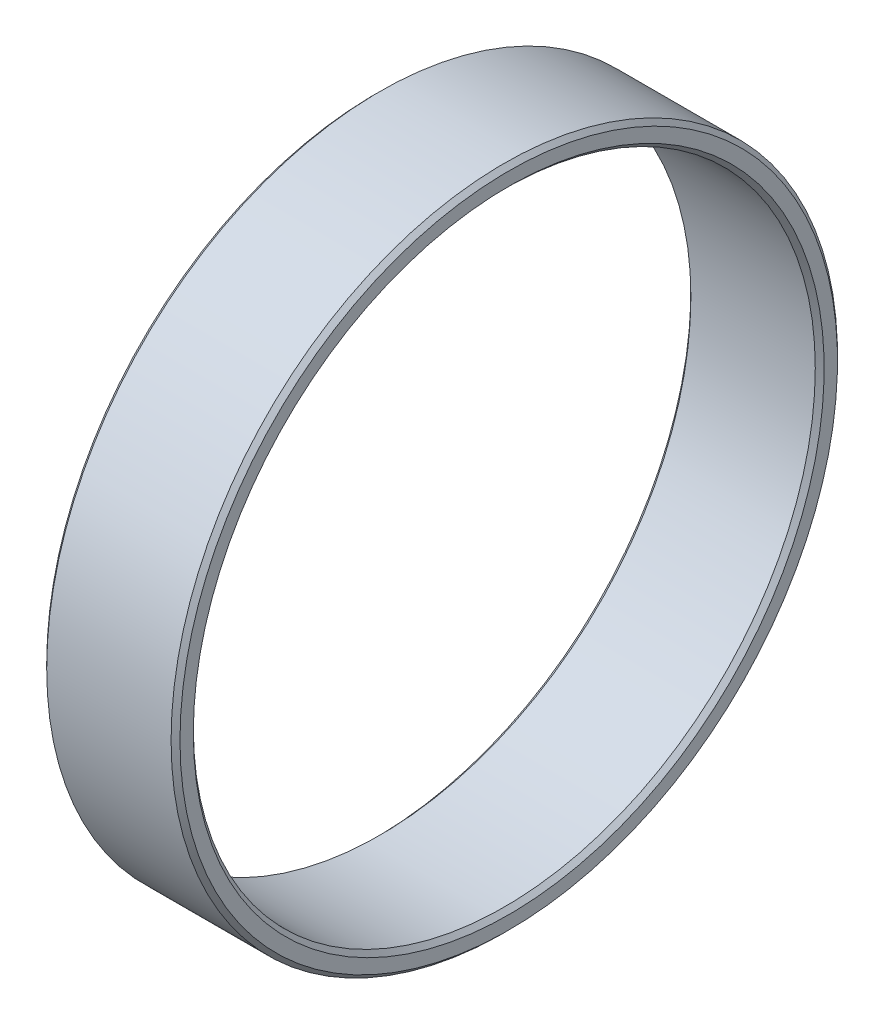
SolidWorks part; units mm, degrees
material "AISI 304"
ref_plane "Front Plane" through (0, 0, 0) normal (0, 0, 1) x (1, 0, 0)
ref_plane "Top Plane" through (0, 0, 0) normal (0, 1, 0) x (1, 0, 0)
ref_plane "Right Plane" through (0, 0, 0) normal (1, 0, 0) x (0, 0, -1)
sketch "Sketch1" plane through (0, 0, 0) normal (0, 0, 1) x (1, 0, 0)
  line L0 (0, 0) -> (15, 0) construction
  line L1 (0, 37) -> (0.5, 37.5)
  line L2 (0.5, 35) -> (14.5, 35)
  line L3 (0, 35.5) -> (0, 37)
  line L4 (0.5, 37.5) -> (14.5, 37.5)
  line L5 (15, 35.5) -> (15, 37)
  line L6 (0, 35.5) -> (0.5, 35)
  line L7 (14.5, 37.5) -> (15, 37)
  line L8 (14.5, 35) -> (15, 35.5)
  point P3 (0, 35)
  point P4 (15, 37.5)
  point P5 (0, 37.5)
  point P6 (15, 35)
  dimension "D1" = 15
  dimension "D2" = 75
  dimension "D3" = 70
  dimension "D4" = 0.5
  dimension "D5" = 45
  dimension "D6" = 0.5
  dimension "D7" = 45
  dimension "D8" = 0.5
  dimension "D9" = 45
  dimension "D10" = 0.5
  dimension "D11" = 45
revolve "Revolve1" add sketch "Sketch1" angle 360 about L0
